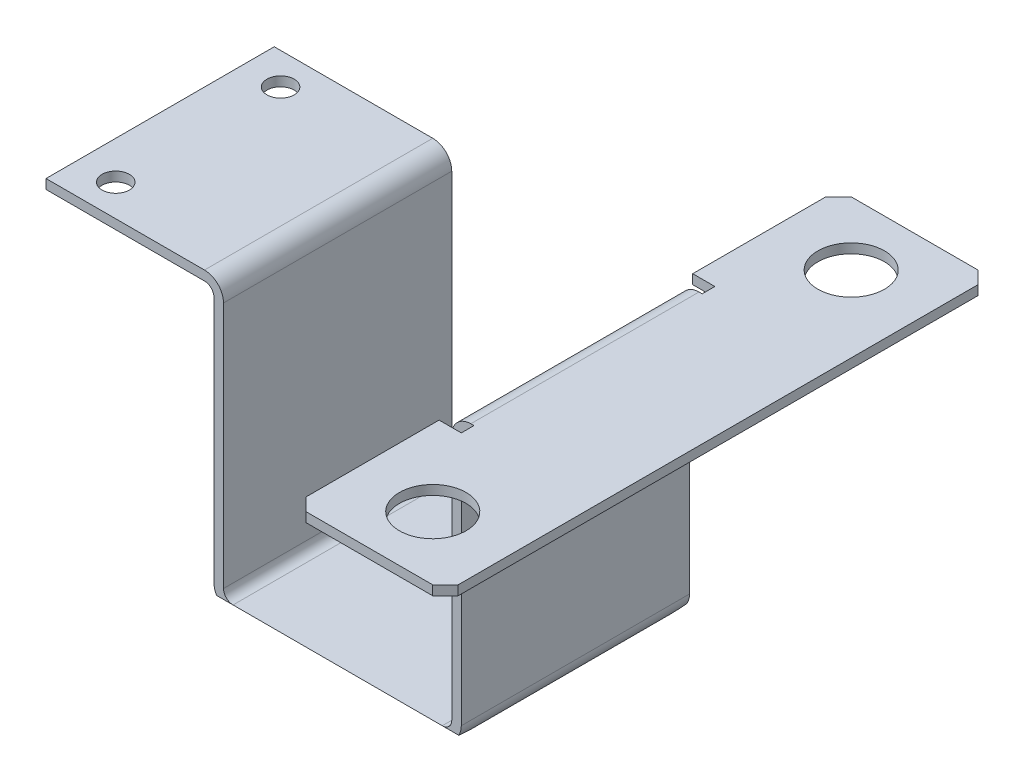
SolidWorks part; units mm, degrees
ref_plane "Спереди" through (0, 0, 0) normal (0, 0, 1) x (1, 0, 0)
ref_plane "Сверху" through (0, 0, 0) normal (0, 1, 0) x (1, 0, 0)
ref_plane "Справа" through (0, 0, 0) normal (1, 0, 0) x (0, 0, -1)
sketch "Эскиз1" plane through (0, 0, 0) normal (0, 0, 1) x (1, 0, 0)
  line L0 (-32, 43.5) -> (0, 43.5)
  line L1 (0, 43.5) -> (0, 0)
  line L2 (0, 0) -> (36, 0)
  line L3 (36, 0) -> (36, 43.5)
  line L4 (37.5, -1.5) -> (37.5, 42)
  line L5 (-1.5, -1.5) -> (37.5, -1.5)
  line L6 (-1.5, 42) -> (-1.5, -1.5)
  line L7 (-32, 42) -> (-1.5, 42)
  line L8 (-32, 42) -> (-32, 43.5)
  line L9 (60, 43.5) -> (36, 43.5)
  line L13 (37.5, 42) -> (60, 42)
  line L14 (60, 43.5) -> (60, 42)
  dimension "D1" = 36
  dimension "D2" = 1.5
  dimension "D3" = 45
  dimension "D4" = 68
  dimension "D5" = 1.5
  dimension "D6" = 61.5
  dimension "D7" = 45
extrude "Вытянуть1" add sketch "Эскиз1" along normal blind 36
sketch "Эскиз2" plane through (0, 43.5, 0) normal (0, 1, 0) x (-1, 0, 0)
  line L0 (-32.6135, 18) -> (24.3521, 18) construction
  line L1 (0, 0) -> (32, 0) construction
  line L2 (0, 36) -> (32, 36) construction
  line L3 (-36, 0) -> (0, 0) construction
  line L4 (-36, 36) -> (0, 36) construction
  line L5 (22, -5.6921) -> (22, 38.3004) construction
  line L6 (32, 36) -> (32, 0) construction
  circle A0 centre (22, 5) radius 2.15
  circle A1 centre (22, 31) radius 2.15
  dimension "D2" = 26
  dimension "D3" = 4.3
  dimension "D1" = 10
extrude "Вырез-Вытянуть1" cut sketch "Эскиз2" against normal blind 35
fillet "Скругление1" radius 1.5 3 edges at (36, 0, 18) (0, 0, 18) (-1.5, 42, 18)
fillet "Скругление2" radius 3 3 edges at (-1.5, -1.5, 18) (37.5, -1.5, 18) (0, 43.5, 18)
sketch "Эскиз4" plane through (-1.5, 0, 0) normal (-1, 0, 0) x (0, 0, 1)
  line L0 (36, 0) -> (30.4019, -1.5)
  line L1 (36, -1.5) -> (0, -1.5) construction
  line L2 (18, 25.5007) -> (18, -4.2731) construction
  line L3 (36, 40.5) -> (36, 1.5) construction
  line L4 (0, 40.5) -> (0, 1.5) construction
  line L5 (0, 0) -> (5.5981, -1.5)
  line L6 (36, 0) -> (36, -8.931)
  line L7 (36, -8.931) -> (0, -9.7268)
  line L8 (0, -9.7268) -> (0, 0)
  line L9 (5.5981, -1.5) -> (30.4019, -1.5)
  dimension "D1" = 15
extrude "Вырез-Вытянуть5" cut sketch "Эскиз4" against normal blind 50
sketch "Эскиз5" plane through (0, 43.5, 0) normal (0, 1, 0) x (-1, 0, 0)
  line L0 (-63.6407, 18) -> (21.0689, 18) construction
  line L1 (-60, 0) -> (-36, 0) construction
  line L2 (-60, 36) -> (-36, 36) construction
  line L3 (-60, 36) -> (-60, 0) construction
  line L4 (-36, -25) -> (-60, -25)
  line L5 (-36, -25) -> (-36, 61)
  line L6 (-36, 61) -> (-60, 61)
  line L7 (-60, -25) -> (-60, 61)
  line L8 (-36, 36) -> (-36, 0) construction
  line L9 (-48, -35.3655) -> (-48, 64.7752) construction
  circle A0 centre (-48, -15) radius 5.25
  circle A1 centre (-48, 51) radius 5.25
  dimension "D1" = 10.5
  dimension "D2" = 33
  dimension "D3" = 86
extrude "Вытянуть2" add sketch "Эскиз5" against normal blind 1.5
sketch "Эскиз6" plane through (36, 0, 0) normal (-1, 0, 0) x (0, 0, 1)
  line L0 (36, 42) -> (36, 1.5) construction
  line L1 (36, 39.7705) -> (38, 39.7705)
  line L2 (36, 39.7705) -> (36, 46.1069)
  line L3 (36, 46.1069) -> (38, 46.1069)
  line L4 (38, 39.7705) -> (38, 46.1069)
  line L5 (18, 50.7661) -> (18, 23.1839) construction
  line L6 (0, 42) -> (0, 1.5) construction
  line L7 (0, 39.7705) -> (0, 46.1069)
  line L8 (0, 46.1069) -> (-2, 46.1069)
  line L9 (-2, 39.7705) -> (-2, 46.1069)
  line L10 (0, 39.7705) -> (-2, 39.7705)
  dimension "D1" = 2
extrude "Вырез-Вытянуть6" cut sketch "Эскиз6" against normal blind 3.5
fillet "Скругление3" radius 1.5 1 edges at (37.5, 42, 18)
fillet "Скругление4" radius 3 1 edges at (36, 43.5, 18)
chamfer "Фаска1" distance 2 angle 45 4 edges at (36, 42.75, 61) (60, 42.75, 61) (60, 42.75, -25) (36, 42.75, -25)
sketch "Эскиз7" plane through (-32, 0, 0) normal (-1, 0, 0) x (0, 0, 1)
  line L4 (0, 43.5) -> (0, 42)
  line L5 (0, 42) -> (36, 42)
  line L6 (36, 42) -> (36, 43.5)
  line L7 (36, 43.5) -> (0, 43.5)
  line L8 (0, 43.5) -> (0, 42)
  line L9 (0, 42) -> (36, 42)
  line L10 (36, 42) -> (36, 43.5)
  line L11 (36, 43.5) -> (0, 43.5)
  dimension "D1" = 0
extrude "Вырез-Вытянуть7" cut sketch "Эскиз7" against normal blind 4
